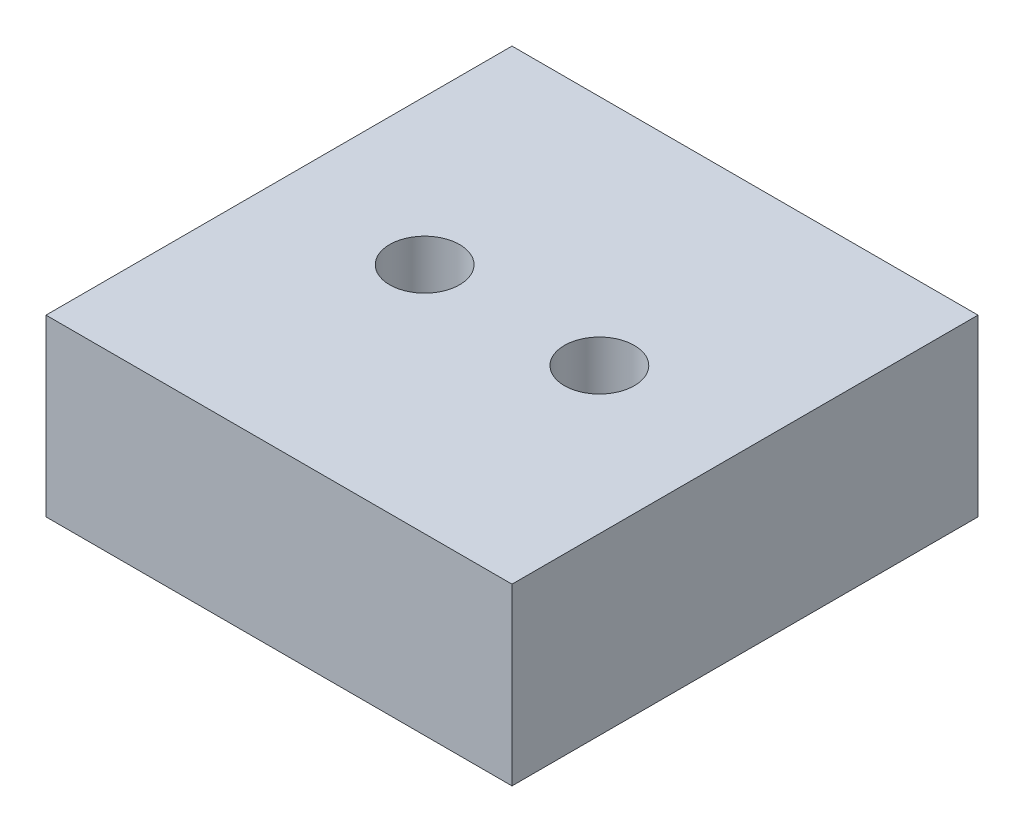
SolidWorks part; units mm, degrees
ref_plane "Front Plane" through (0, 0, 0) normal (0, 0, 1) x (1, 0, 0)
ref_plane "Top Plane" through (0, 0, 0) normal (0, 1, 0) x (1, 0, 0)
ref_plane "Right Plane" through (0, 0, 0) normal (1, 0, 0) x (0, 0, -1)
sketch "Sketch1" plane through (0, 0, 0) normal (0, 1, 0) x (1, 0, 0)
  line L1 (-20, 20) -> (20, 20)
  line L2 (-20, 20) -> (-20, -20)
  line L3 (-20, -20) -> (20, -20)
  line L4 (20, 20) -> (20, -20)
  circle A0 centre (-7.5, 0) radius 3
  circle A1 centre (7.5, 0) radius 3
  point P4 (0, 20)
  point P6 (20, 0)
  dimension "D3" = 6
  dimension "D4" = 6
  dimension "D1" = 40
  dimension "D2" = 40
  dimension "D5" = 15
  dimension "D6" = 7.5
extrude "Boss-Extrude1" add sketch "Sketch1" along normal blind 15
